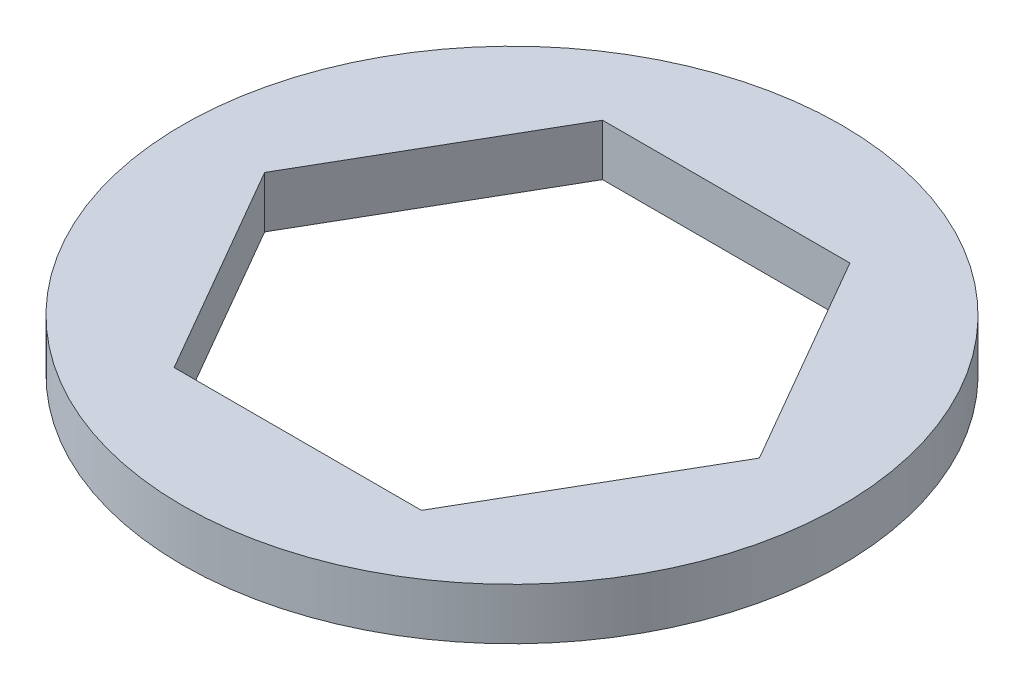
SolidWorks part; units mm, degrees
material "PET"
ref_plane "Front Plane" through (0, 0, 0) normal (0, 0, 1) x (1, 0, 0)
ref_plane "Top Plane" through (0, 0, 0) normal (0, 1, 0) x (1, 0, 0)
ref_plane "Right Plane" through (0, 0, 0) normal (1, 0, 0) x (0, 0, -1)
sketch "Sketch1" plane through (0, 0, 0) normal (0, 1, 0) x (1, 0, 0)
  line L1 (7.6256, 0) -> (3.8128, 6.604)
  line L2 (3.8128, 6.604) -> (-3.8128, 6.604)
  line L3 (-3.8128, 6.604) -> (-7.6256, 0)
  line L4 (-7.6256, 0) -> (-3.8128, -6.604)
  line L5 (-3.8128, -6.604) -> (3.8128, -6.604)
  line L6 (3.8128, -6.604) -> (7.6256, 0)
  circle A0 centre (0, 0) radius 10.16
  circle A1 centre (0, 0) radius 6.604 construction
  dimension "D1" = 13.208
  dimension "D2" = 20.32
extrude "Boss-Extrude1" add sketch "Sketch1" along normal mid plane 1.5875
